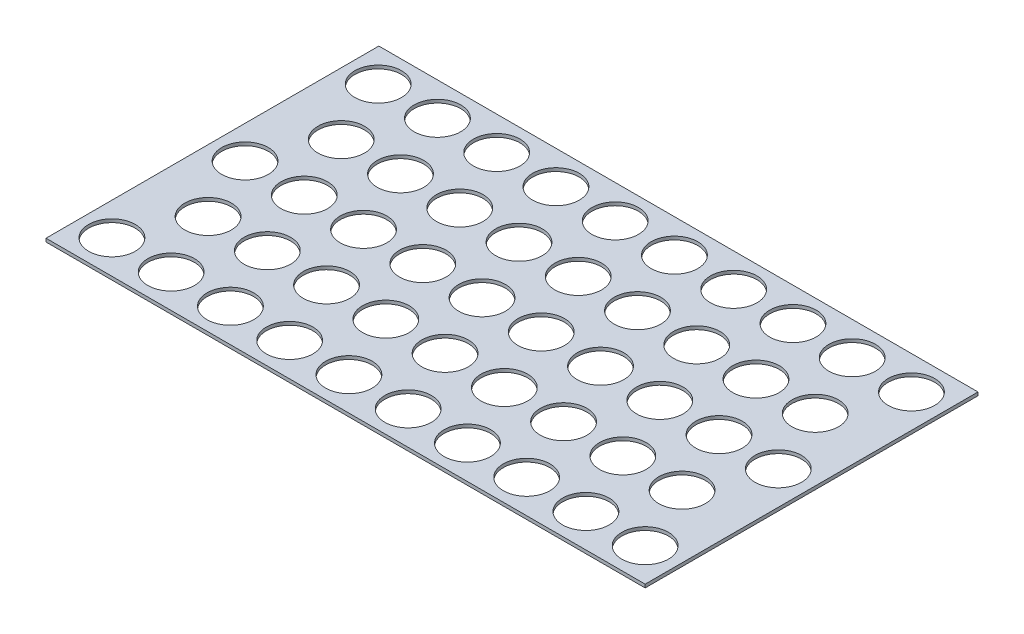
SolidWorks part; units mm, degrees
ref_plane "Front Plane" through (0, 0, 0) normal (0, 0, 1) x (1, 0, 0)
ref_plane "Top Plane" through (0, 0, 0) normal (0, 1, 0) x (1, 0, 0)
ref_plane "Right Plane" through (0, 0, 0) normal (1, 0, 0) x (0, 0, -1)
sketch "Sketch1" plane through (0, 0, 0) normal (0, 1, 0) x (1, 0, 0)
  line L5 (-87.8852, 21.7835) -> (140.7148, 21.7835)
  line L6 (-87.8852, 21.7835) -> (-87.8852, -105.2165)
  line L7 (-87.8852, -105.2165) -> (140.7148, -105.2165)
  line L8 (140.7148, 21.7835) -> (140.7148, -105.2165)
  dimension "D1" = 228.6
  dimension "D2" = 127
extrude "Boss-Extrude1" add sketch "Sketch1" along normal blind 1.27 contours L6 L5 L8 L7
sketch "Sketch2" plane through (0, 1.27, 0) normal (0, 1, 0) x (1, 0, 0)
  line L0 (140.7148, 21.7835) -> (140.7148, 9.0835) construction
  line L1 (140.7148, 21.7835) -> (140.7148, -105.2165) construction
  line L2 (140.7148, 9.0835) -> (128.0148, 9.0835) construction
  line L5 (128.0148, 9.0835) -> (128.0148, -16.3165) construction
  line L6 (128.0148, -16.3165) -> (116.7118, -16.3165) construction
  circle A0 centre (128.0148, 9.0835) radius 8.89
  circle A30 centre (105.4088, 9.0835) radius 8.89
  circle A31 centre (82.8028, 9.0835) radius 8.89
  circle A32 centre (60.1968, 9.0835) radius 8.89
  circle A33 centre (37.5908, 9.0835) radius 8.89
  circle A34 centre (14.9848, 9.0835) radius 8.89
  circle A35 centre (-7.6212, 9.0835) radius 8.89
  circle A36 centre (-30.2272, 9.0835) radius 8.89
  circle A37 centre (-52.8332, 9.0835) radius 8.89
  circle A47 centre (-75.4392, 9.0835) radius 8.89
  circle A48 centre (128.0148, -41.7165) radius 8.89
  circle A49 centre (128.0148, -92.5165) radius 8.89
  circle A50 centre (105.4088, -41.7165) radius 8.89
  circle A51 centre (105.4088, -92.5165) radius 8.89
  circle A52 centre (82.8028, -41.7165) radius 8.89
  circle A53 centre (82.8028, -92.5165) radius 8.89
  circle A54 centre (60.1968, -41.7165) radius 8.89
  circle A55 centre (60.1968, -92.5165) radius 8.89
  circle A56 centre (37.5908, -41.7165) radius 8.89
  circle A57 centre (37.5908, -92.5165) radius 8.89
  circle A58 centre (14.9848, -41.7165) radius 8.89
  circle A59 centre (14.9848, -92.5165) radius 8.89
  circle A60 centre (-7.6212, -41.7165) radius 8.89
  circle A61 centre (-7.6212, -92.5165) radius 8.89
  circle A62 centre (-30.2272, -41.7165) radius 8.89
  circle A63 centre (-30.2272, -92.5165) radius 8.89
  circle A64 centre (-52.8332, -41.7165) radius 8.89
  circle A65 centre (-52.8332, -92.5165) radius 8.89
  circle A66 centre (-75.4392, -41.7165) radius 8.89
  circle A67 centre (-75.4392, -92.5165) radius 8.89
  circle A68 centre (116.7118, -16.3165) radius 8.89
  circle A69 centre (116.7118, -67.1165) radius 8.89
  circle A70 centre (94.1058, -16.3165) radius 8.89
  circle A71 centre (94.1058, -67.1165) radius 8.89
  circle A72 centre (71.4998, -16.3165) radius 8.89
  circle A73 centre (71.4998, -67.1165) radius 8.89
  circle A74 centre (48.8938, -16.3165) radius 8.89
  circle A75 centre (48.8938, -67.1165) radius 8.89
  circle A76 centre (26.2878, -16.3165) radius 8.89
  circle A77 centre (26.2878, -67.1165) radius 8.89
  circle A78 centre (3.6818, -16.3165) radius 8.89
  circle A79 centre (3.6818, -67.1165) radius 8.89
  circle A80 centre (-18.9242, -16.3165) radius 8.89
  circle A81 centre (-18.9242, -67.1165) radius 8.89
  circle A82 centre (-41.5302, -16.3165) radius 8.89
  circle A83 centre (-41.5302, -67.1165) radius 8.89
  circle A84 centre (-64.1362, -16.3165) radius 8.89
  circle A85 centre (-64.1362, -67.1165) radius 8.89
  dimension "D3" = 17.78
  dimension "D10" = 17.78
  dimension "D1" = 12.7
  dimension "D2" = 12.7
  dimension "D6" = 22.606
  dimension "D7" = 10
  dimension "D8" = 25.4
  dimension "D9" = 11.303
  dimension "D4" = 10
  dimension "D5" = 3
  dimension "D11" = 2
  dimension "D12" = 9
extrude "Cut-Extrude1" cut sketch "Sketch2" against normal through all both and the other way through all contours A47 | A37 | A36 | A35 | A34 | A33 | A32 | A31 | A0 | A30 | A68 | A70 | A72 | A74 | A76 | A78 | A80 | A82 | A84 | A66 | A64 | A62 | A60 | A58 | A56 | A54 | A52 | A50 | A48 | A69 | A71 | A73 | A75 | A77 | A79 | A81 | A83 | A85 | A67 | A65 | A63 | A61 | A59 | A57 | A55 | A53 | A51 | A49
